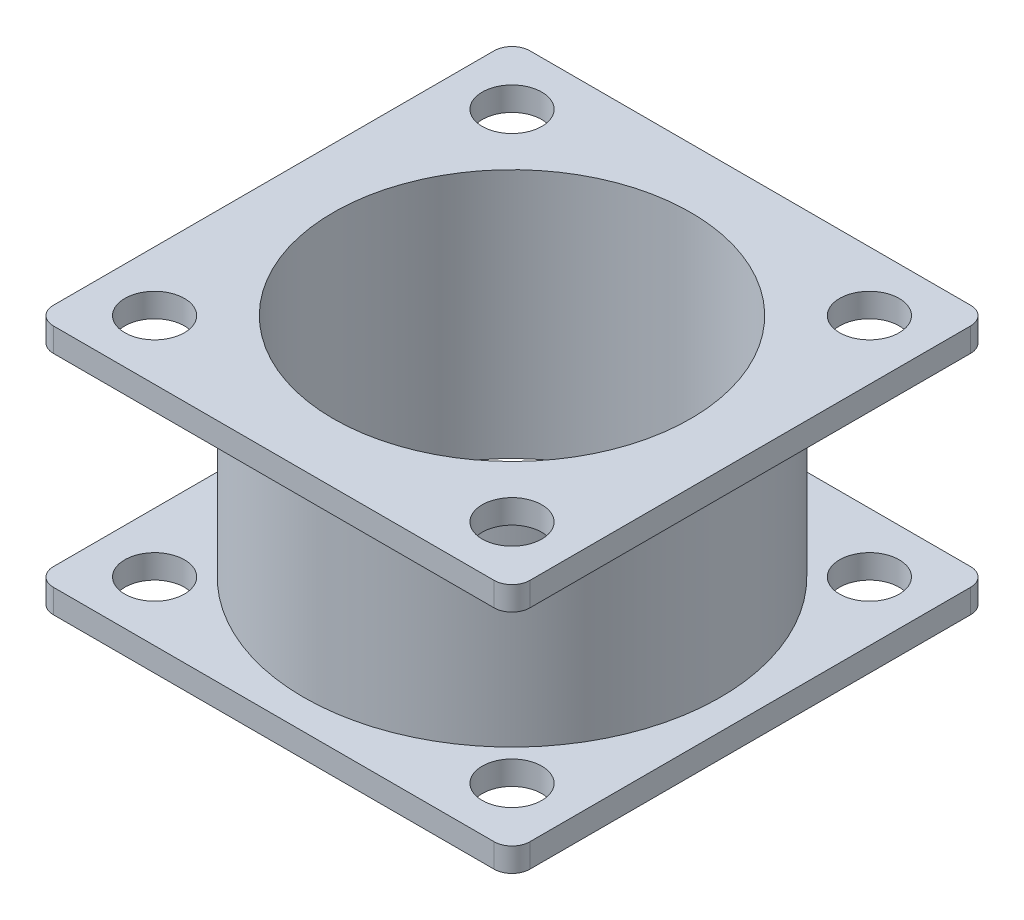
SolidWorks part; units mm, degrees
ref_plane "Front Plane" through (0, 0, 0) normal (0, 0, 1) x (1, 0, 0)
ref_plane "Top Plane" through (0, 0, 0) normal (0, 1, 0) x (1, 0, 0)
ref_plane "Right Plane" through (0, 0, 0) normal (1, 0, 0) x (0, 0, -1)
sketch "Sketch1" plane through (0, 0, 0) normal (0, 1, 0) x (1, 0, 0)
  line L1 (40, -40) -> (-40, -40)
  line L2 (40, -40) -> (40, 40)
  line L3 (40, 40) -> (-40, 40)
  line L4 (-40, -40) -> (-40, 40)
  point P0 (0, 0)
  dimension "D1" = 80
  dimension "D2" = 80
extrude "Boss-Extrude1" add sketch "Sketch1" along normal blind 4
fillet "Fillet3" radius 3 1 edges at (40, 2, 40)
fillet "Fillet2" radius 3 3 edges at (40, 2, -40) (-40, 2, -40) (-40, 2, 40)
sketch "Sketch3" plane through (0, 4, 0) normal (0, 1, 0) x (1, 0, 0)
  circle A0 centre (0, 0) radius 35
extrude "Boss-Extrude3" add sketch "Sketch3" along normal blind 17 contours A0
mirror "Mirror1" about plane through (0, 21, 0) normal (0, 1, 0) of "Boss-Extrude3", "Boss-Extrude1"
sketch "Sketch4" plane through (0, 38, 0) normal (0, 1, 0) x (1, 0, 0)
  line L5 (40, -40) -> (-40, -40)
  line L6 (40, -40) -> (40, 40)
  line L7 (40, 40) -> (-40, 40)
  line L8 (-40, -40) -> (-40, 40)
  line L9 (40, -40) -> (-40, 40) construction
  line L10 (40, 40) -> (-40, -40) construction
  point P0 (0, 0)
  point P1 (0, 0)
  dimension "D1" = 80
  dimension "D2" = 80
extrude "Boss-Extrude4" add sketch "Sketch4" along normal blind 4
fillet "Fillet4" radius 3 4 edges at (40, 40, 40) (40, 40, -40) (-40, 40, -40) (-40, 40, 40)
sketch "Sketch5" plane through (0, 42, 0) normal (0, 1, 0) x (1, 0, 0)
  circle A0 centre (0, 0) radius 30
extrude "Cut-Extrude1" cut sketch "Sketch5" against normal through all
sketch "Sketch6" plane through (0, 42, 0) normal (0, 1, 0) x (1, 0, 0)
  line L0 (0, 0) -> (0, 30)
  line L1 (0, 30) -> (30, 30)
  circle A0 centre (30, 30) radius 5
  circle A1 centre (30, -30) radius 5
  circle A2 centre (-30, -30) radius 5
  circle A3 centre (-30, 30) radius 5
  point P14 (0, 0)
  dimension "D3" = 4
  dimension "D1" = 30
  dimension "D2" = 30
extrude "Cut-Extrude2" cut sketch "Sketch6" against normal through all contours A3 | A0 | A1 | A2
